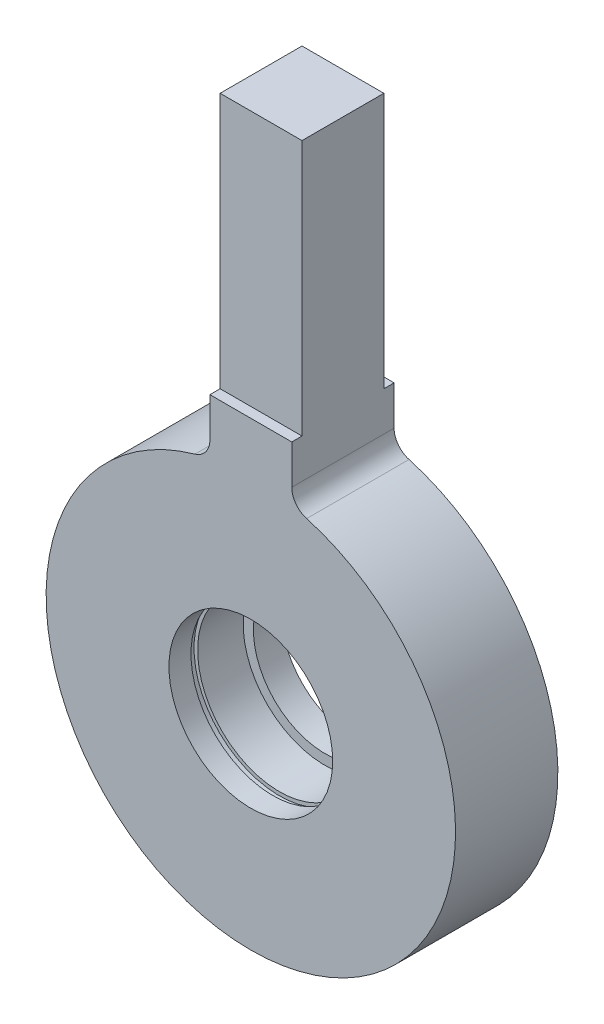
SolidWorks part; units mm, degrees
ref_plane "Front Plane" through (0, 0, 0) normal (0, 0, 1) x (1, 0, 0)
ref_plane "Top Plane" through (0, 0, 0) normal (0, 1, 0) x (1, 0, 0)
ref_plane "Right Plane" through (0, 0, 0) normal (1, 0, 0) x (0, 0, -1)
sketch "Sketch1" plane through (0, 0, 0) normal (0, 0, 1) x (1, 0, 0)
  circle A0 centre (0, 0) radius 14
  circle A1 centre (0, 0) radius 40
  dimension "D1" = 28
  dimension "D2" = 80
extrude "Boss-Extrude1" add sketch "Sketch1" along normal mid plane 20
sketch "Sketch2" plane through (0, 0, 0) normal (0, 0, 1) x (1, 0, 0)
  line L0 (0, 0) -> (0, 75.4968) construction
  line L1 (-8, 100) -> (8, 100)
  line L2 (8, 100) -> (8, 39.1918)
  line L3 (-8, 100) -> (-8, 39.1918)
  line L4 (-8, 39.1918) -> (8, 39.1918)
  circle A0 centre (0, 0) radius 40 construction
  point P10 (0, 100)
  dimension "D1" = 16
  dimension "D2" = 100
extrude "Boss-Extrude2" add sketch "Sketch2" along normal mid plane 20
fillet "Fillet1" radius 4 2 edges at (-8, 39.1918, 0) (8, 39.1918, 0)
sketch "Sketch3" plane through (0, 0, 0) normal (1, 0, 0) x (0, 0, -1)
  line L0 (0, 0) -> (36.2767, 0) construction
  line L1 (4.5, 14) -> (4.5, 16)
  line L2 (10, 14) -> (-10, 14) construction
  line L3 (4.5, 16) -> (-10, 16)
  line L4 (-10, 38.4837) -> (-10, -40) construction
  line L5 (-10, 16) -> (-10, 14)
  line L6 (-10, 14) -> (4.5, 14)
  dimension "D1" = 16
  dimension "D2" = 4.5
revolve "Cut-Revolve1" cut sketch "Sketch3" angle 360 about L0
sketch "Sketch4" plane through (0, 0, 0) normal (1, 0, 0) x (0, 0, -1)
  line L0 (0, 0) -> (28.6469, 0) construction
  line L1 (-4.4, 16) -> (-4.4, 16.7)
  line L2 (4.5, 16) -> (-10, 16) construction
  line L3 (-4.4, 16.7) -> (-5.7, 16.7)
  line L4 (-5.7, 16.7) -> (-5.7, 16)
  line L5 (-5.7, 16) -> (-4.4, 16)
  line L6 (4.5, 16) -> (4.5, -16) construction
  dimension "D1" = 16.7
  dimension "D2" = 10.2
  dimension "D3" = 1.3
revolve "Cut-Revolve2" cut sketch "Sketch4" angle 360 about L0
sketch "Sketch5" plane through (0, 0, 0) normal (1, 0, 0) x (0, 0, -1)
  line L0 (0, 0) -> (0, 101.1031) construction
  line L1 (8, 100) -> (8, 50)
  line L2 (-10, 100) -> (10, 100) construction
  line L3 (8, 50) -> (10, 50)
  line L4 (10, 42.332) -> (10, 100) construction
  line L5 (10, 50) -> (10, 100)
  line L6 (10, 100) -> (8, 100)
  line L7 (-8, 50) -> (-10, 50)
  line L8 (-10, 50) -> (-10, 100)
  line L9 (-10, 100) -> (-8, 100)
  line L10 (-8, 100) -> (-8, 50)
  dimension "D1" = 50
  dimension "D2" = 16
extrude "Cut-Extrude1" cut sketch "Sketch5" against normal through all both and the other way through all
sketch "Sketch7" [suppressed] plane through (0, 0, 0) normal (0, 1, 0) x (1, 0, 0)
  line L1 (0, 14.1597) -> (50.6809, 14.1597)
  line L2 (0, 14.1597) -> (0, -19.3087)
  line L3 (0, -19.3087) -> (50.6809, -19.3087)
  line L4 (50.6809, 14.1597) -> (50.6809, -19.3087)
extrude "Cut-Extrude2" [suppressed] cut sketch "Sketch7" against normal through all both and the other way through all
